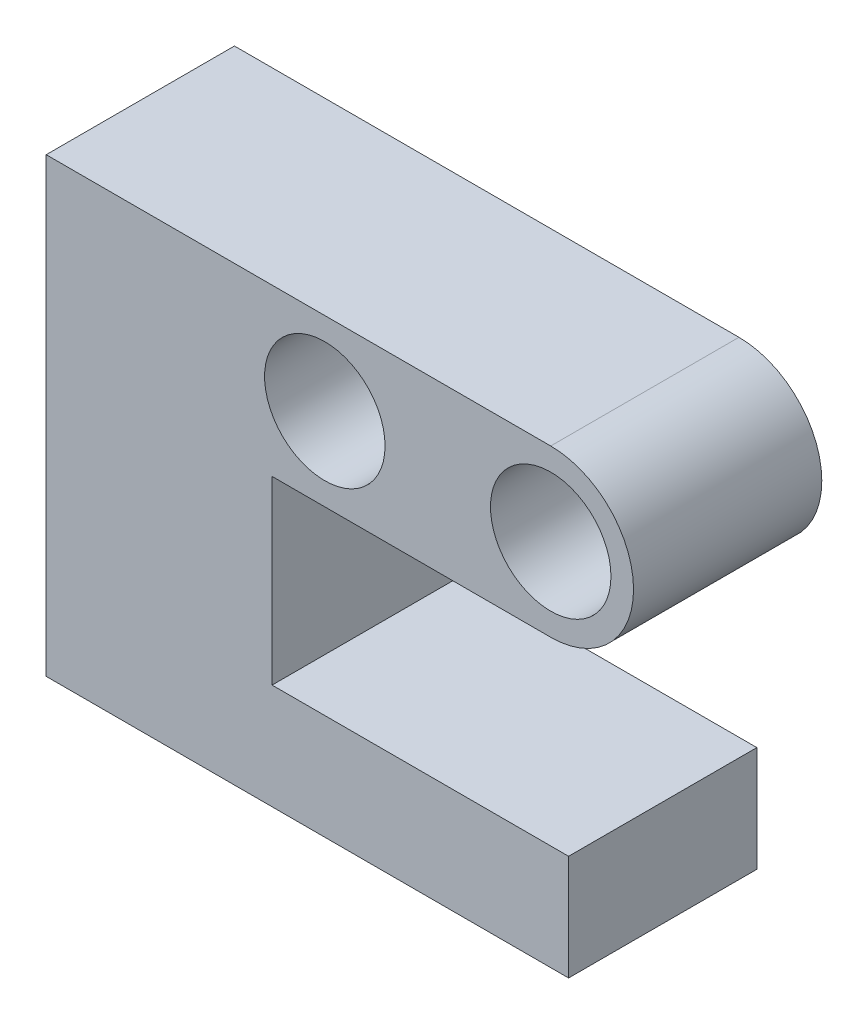
SolidWorks part; units mm, degrees
ref_plane "Front Plane" through (0, 0, 0) normal (0, 0, 1) x (1, 0, 0)
ref_plane "Top Plane" through (0, 0, 0) normal (0, 1, 0) x (1, 0, 0)
ref_plane "Right Plane" through (0, 0, 0) normal (1, 0, 0) x (0, 0, -1)
sketch "Sketch1" plane through (0, 0, 0) normal (0, 0, 1) x (1, 0, 0)
  line L0 (-30, 11) -> (0, 11)
  line L1 (-30, -11) -> (0, -11)
  line L2 (-30, 11) -> (-67, 11)
  line L3 (-67, 11) -> (-67, -49)
  line L4 (-67, -49) -> (-37, -49)
  line L5 (-37, -49) -> (2.3742, -49)
  line L6 (-37, -11) -> (-30, -11)
  line L7 (2.3742, -49) -> (2.3742, -35)
  line L8 (2.3742, -35) -> (-37, -35)
  line L9 (-37, -35) -> (-37, -11)
  circle A2 centre (0, 0) radius 8
  circle A3 centre (-30, 0) radius 8
  arc A5 (0, -11) -> (0, 11) centre (0, 0) ccw
  point P1 (-15, -11)
  dimension "D2" = 22
  dimension "D3" = 16
  dimension "D4" = 16
  dimension "D5" = 30
  dimension "D1" = 30
  dimension "D6" = 60
  dimension "D7" = 24
extrude "Boss-Extrude1" add sketch "Sketch1" along normal blind 25
sketch "Sketch2" plane through (-67, 0, 0) normal (-1, 0, 0) x (0, 0, 1)
  line L0 (12.5, 11) -> (12.5, 1) construction
  line L1 (25, 11) -> (0, 11) construction
  line L2 (12.5, 1) -> (12.5, -39) construction
  line L3 (12.5, -39) -> (12.5, -49) construction
  line L4 (25, -49) -> (0, -49) construction
  circle A0 centre (12.5, 1) radius 4
  circle A1 centre (12.5, -39) radius 4
  dimension "D1" = 8
  dimension "D2" = 8
  dimension "D3" = 40
extrude "Cut-Extrude1" cut sketch "Sketch2" against normal blind 17
